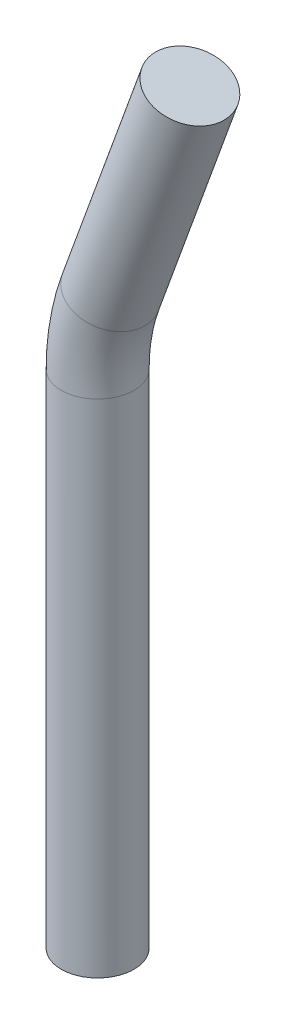
SolidWorks part; units mm, degrees
ref_plane "Front Plane" through (0, 0, 0) normal (0, 0, 1) x (1, 0, 0)
ref_plane "Top Plane" through (0, 0, 0) normal (0, 1, 0) x (1, 0, 0)
ref_plane "Right Plane" through (0, 0, 0) normal (1, 0, 0) x (0, 0, -1)
sketch "Sketch1" plane through (0, 0, 0) normal (0, 0, 1) x (1, 0, 0)
  line L0 (0, 0) -> (0, 92.9469)
  line L1 (2.4123, 106.6277) -> (17.101, 146.9846)
  arc A0 (0, 92.9469) -> (2.4123, 106.6277) centre (40, 92.9469) cw
  point P6 (0, 100)
  dimension "D3" = 40
  dimension "D1" = 50
  dimension "D2" = 100
  dimension "D4" = 160
sketch "Sketch2" plane through (0, 0, 0) normal (0, 1, 0) x (1, 0, 0)
  circle A0 centre (0, 0) radius 6.75
  dimension "D1" = 13.5
sweep "Sweep1" add profiles "Sketch2" path "Sketch1"
